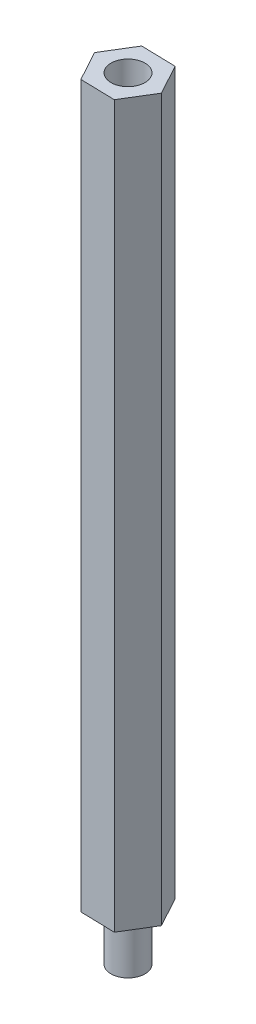
SolidWorks part; units mm, degrees
ref_plane "정면" through (0, 0, 0) normal (0, 0, 1) x (1, 0, 0)
ref_plane "윗면" through (0, 0, 0) normal (0, 1, 0) x (1, 0, 0)
ref_plane "우측면" through (0, 0, 0) normal (1, 0, 0) x (0, 0, -1)
sketch "스케치1" plane through (0, 0, 0) normal (0, 1, 0) x (1, 0, 0)
  line L1 (1.9316, -3.55) -> (4.0402, -0.1022)
  line L2 (4.0402, -0.1022) -> (2.1086, 3.4478)
  line L3 (2.1086, 3.4478) -> (-1.9316, 3.55)
  line L4 (-1.9316, 3.55) -> (-4.0402, 0.1022)
  line L5 (-4.0402, 0.1022) -> (-2.1086, -3.4478)
  line L6 (-2.1086, -3.4478) -> (1.9316, -3.55)
  circle A0 centre (0, 0) radius 3.5 construction
  dimension "D1" = 7
extrude "보스-돌출1" add sketch "스케치1" along normal blind 85
sketch "스케치2" plane through (0, 85, 0) normal (0, 1, 0) x (1, 0, 0)
  circle A0 centre (0, 0) radius 2
  dimension "D1" = 4
extrude "컷-돌출1" cut sketch "스케치2" against normal blind 8
sketch "스케치3" plane through (0, 0, 0) normal (0, -1, 0) x (1, 0, 0)
  circle A0 centre (0, 0) radius 2
  dimension "D1" = 4
extrude "보스-돌출2" add sketch "스케치3" along normal blind 6
